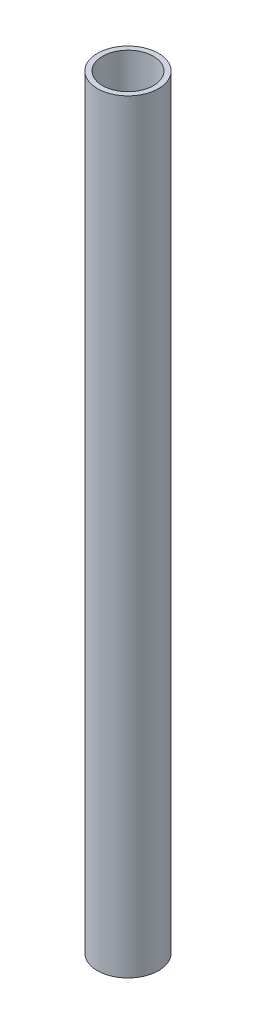
SolidWorks part; units mm, degrees
material "Thornel Mat VMA"
ref_plane "前视基准面" through (0, 0, 0) normal (0, 0, 1) x (1, 0, 0)
ref_plane "上视基准面" through (0, 0, 0) normal (0, 1, 0) x (1, 0, 0)
ref_plane "右视基准面" through (0, 0, 0) normal (1, 0, 0) x (0, 0, -1)
other "Configuration Table"
sketch "草图1" plane through (0, 0, 0) normal (0, 1, 0) x (1, 0, 0)
  circle A0 centre (0, 0) radius 5
  circle A1 centre (0, 0) radius 6
  dimension "D1" = 10
  dimension "D2" = 1
extrude "凸台-拉伸1" add sketch "草图1" along normal blind 150
